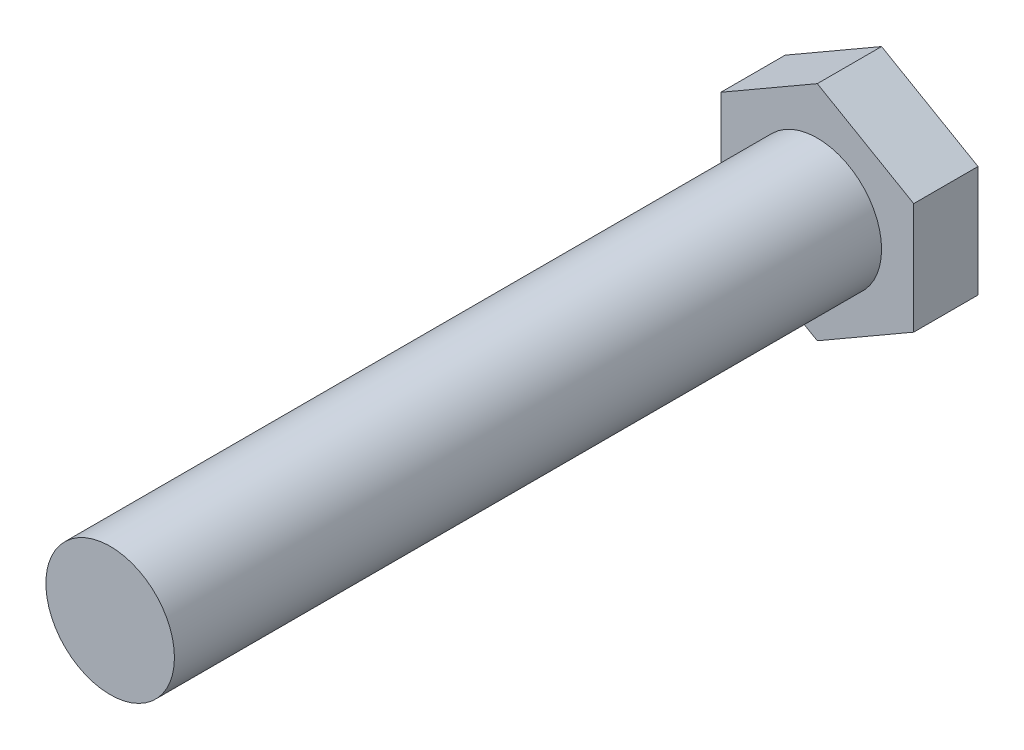
SolidWorks part; units mm, degrees
material "Alloy Steel (SS)"
ref_plane "Front Plane" through (0, 0, 0) normal (0, 0, 1) x (1, 0, 0)
ref_plane "Top Plane" through (0, 0, 0) normal (0, 1, 0) x (1, 0, 0)
ref_plane "Right Plane" through (0, 0, 0) normal (1, 0, 0) x (0, 0, -1)
sketch "Sketch1" plane through (0, 0, 0) normal (0, 0, 1) x (1, 0, 0)
  line L0 (0, 0) -> (0, 8.6603) construction
  line L2 (0, 8.6603) -> (-7.5, 4.3301)
  line L3 (-7.5, 4.3301) -> (-7.5, -4.3301)
  line L4 (-7.5, -4.3301) -> (0, -8.6603)
  line L5 (0, -8.6603) -> (7.5, -4.3301)
  line L6 (7.5, -4.3301) -> (7.5, 4.3301)
  line L7 (7.5, 4.3301) -> (0, 8.6603)
  circle A0 centre (0, 0) radius 7.5 construction
  circle A1 centre (0, 0) radius 5 construction
  dimension "D1" = 10
  dimension "D2" = 2.5
extrude "Boss-Extrude1" add sketch "Sketch1" along normal blind 5
sketch "Sketch2" plane through (0, 0, 5) normal (0, 0, 1) x (1, 0, 0)
  circle A0 centre (0, 0) radius 5
  circle A1 centre (0, 0) radius 5 construction
extrude "Boss-Extrude2" add sketch "Sketch2" along normal blind 55
cosmetic thread "Cosmetic Thread1"
